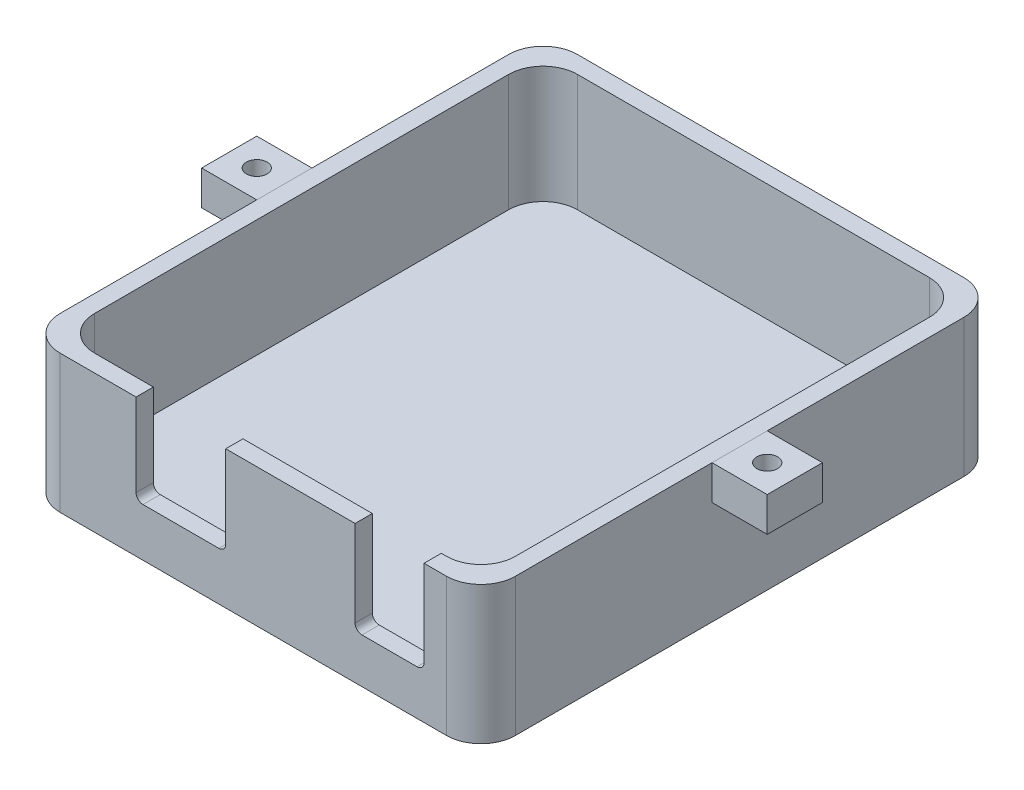
SolidWorks part; units mm, degrees
ref_plane "Ebene vorne" through (0, 0, 0) normal (0, 0, 1) x (1, 0, 0)
ref_plane "Ebene oben" through (0, 0, 0) normal (0, 1, 0) x (1, 0, 0)
ref_plane "Ebene rechts" through (0, 0, 0) normal (1, 0, 0) x (0, 0, -1)
sketch "Skizze1" plane through (0, 0, 0) normal (0, 1, 0) x (1, 0, 0)
  line L1 (28, -37.5) -> (-28, -37.5)
  line L2 (33, -32.5) -> (33, 32.5)
  line L3 (28, 37.5) -> (-28, 37.5)
  line L4 (-33, -32.5) -> (-33, 32.5)
  line L5 (33, -37.5) -> (-33, 37.5) construction
  line L6 (33, 37.5) -> (-33, -37.5) construction
  arc A0 (33, 32.5) -> (28, 37.5) centre (28, 32.5) ccw
  arc A1 (28, -37.5) -> (33, -32.5) centre (28, -32.5) ccw
  arc A2 (-28, -37.5) -> (-33, -32.5) centre (-28, -32.5) cw
  arc A3 (-28, 37.5) -> (-33, 32.5) centre (-28, 32.5) ccw
  point P0 (0, 0)
  dimension "D3" = 5
  dimension "D1" = 75
  dimension "D2" = 66
extrude "Aufsatz-Linear austragen1" add sketch "Skizze1" along normal blind 20
sketch "Skizze2" plane through (0, 20, 0) normal (0, 1, 0) x (1, 0, 0)
  line L0 (28, 37.5) -> (-28, 37.5) construction
  line L1 (-25.5, 35) -> (25.5, 35)
  line L2 (-30.5, 30) -> (-30.5, -30)
  line L3 (-25.5, -35) -> (25.5, -35)
  line L4 (30.5, 30) -> (30.5, -30)
  line L5 (-30.5, 35) -> (30.5, -35) construction
  line L6 (-30.5, -35) -> (30.5, 35) construction
  line L7 (33, -32.5) -> (33, 32.5) construction
  arc A0 (-30.5, -30) -> (-25.5, -35) centre (-25.5, -30) ccw
  arc A1 (25.5, -35) -> (30.5, -30) centre (25.5, -30) ccw
  arc A2 (25.5, 35) -> (30.5, 30) centre (25.5, 30) cw
  arc A3 (-25.5, 35) -> (-30.5, 30) centre (-25.5, 30) ccw
  point P0 (0, 0)
  dimension "D3" = 5
  dimension "D1" = 2.5
  dimension "D2" = 2.5
extrude "Schnitt-Linear austragen1" cut sketch "Skizze2" against normal blind 17
sketch "Skizze4" plane through (0, 0, 37.5) normal (0, 0, 1) x (1, 0, 0)
  line L0 (-28, 0) -> (28, 0) construction
  line L1 (-16, 22) -> (-5, 22)
  line L2 (-17, 21) -> (-17, 8)
  line L3 (-16, 7) -> (-5, 7)
  line L4 (-4, 21) -> (-4, 8)
  line L5 (-17, 22) -> (-4, 7) construction
  line L6 (-17, 7) -> (-4, 22) construction
  line L7 (-33, 20) -> (-33, 0) construction
  line L8 (33, 20) -> (33, 0) construction
  line L9 (15.75, 21.5) -> (23.75, 21.5)
  line L10 (14.75, 20.5) -> (14.75, 7.5)
  line L11 (15.75, 6.5) -> (23.75, 6.5)
  line L12 (24.75, 20.5) -> (24.75, 7.5)
  line L13 (14.75, 21.5) -> (24.75, 6.5) construction
  line L14 (14.75, 6.5) -> (24.75, 21.5) construction
  arc A0 (15.75, 21.5) -> (14.75, 20.5) centre (15.75, 20.5) ccw
  arc A1 (23.75, 21.5) -> (24.75, 20.5) centre (23.75, 20.5) cw
  arc A2 (23.75, 6.5) -> (24.75, 7.5) centre (23.75, 7.5) ccw
  arc A3 (14.75, 7.5) -> (15.75, 6.5) centre (15.75, 7.5) ccw
  arc A4 (-17, 8) -> (-16, 7) centre (-16, 8) ccw
  arc A5 (-5, 7) -> (-4, 8) centre (-5, 8) ccw
  arc A6 (-5, 22) -> (-4, 21) centre (-5, 21) cw
  arc A7 (-16, 22) -> (-17, 21) centre (-16, 21) ccw
  point P0 (-10.5, 14.5)
  point P9 (19.75, 14)
  dimension "D9" = 1
  dimension "D10" = 1
  dimension "D1" = 7
  dimension "D2" = 16
  dimension "D3" = 15
  dimension "D4" = 13
  dimension "D5" = 6.5
  dimension "D6" = 8.25
  dimension "D7" = 15
  dimension "D8" = 10
extrude "Schnitt-Linear austragen2" cut sketch "Skizze4" against normal blind 17
sketch "Skizze5" plane through (0, 20, 0) normal (0, 1, 0) x (1, 0, 0)
  line L3 (33, -32.5) -> (33, 32.5) construction
  line L4 (33, -4) -> (41, -4)
  line L5 (33, -4) -> (33, 4)
  line L6 (33, 4) -> (41, 4)
  line L7 (41, -4) -> (41, 4)
  line L8 (24.75, -37.5) -> (28, -37.5) construction
  line L9 (-33, 32.5) -> (-33, -32.5) construction
  line L10 (-33, 4) -> (-41, 4)
  line L11 (-33, 4) -> (-33, -4)
  line L12 (-33, -4) -> (-41, -4)
  line L13 (-41, 4) -> (-41, -4)
  line L14 (-28, -37.5) -> (-17, -37.5) construction
  dimension "D1" = 8
  dimension "D2" = 8
  dimension "D3" = 33.5
  dimension "D4" = 8
  dimension "D5" = 8
  dimension "D6" = 33.5
extrude "Aufsatz-Linear austragen2" add sketch "Skizze5" against normal blind 5 separate body
sketch "Skizze6" plane through (0, 20, 0) normal (0, 1, 0) x (1, 0, 0)
  line L0 (-33, 4) -> (-41, 4) construction
  line L1 (-41, 4) -> (-41, -4) construction
  line L2 (41, -4) -> (41, 4) construction
  line L3 (41, 4) -> (33, 4) construction
  circle A0 centre (-37, 0) radius 1.5
  circle A1 centre (37, 0) radius 1.5
  dimension "D1" = 3
  dimension "D2" = 3
  dimension "D3" = 4
  dimension "D4" = 4
  dimension "D5" = 4
  dimension "D6" = 4
extrude "Schnitt-Linear austragen3" cut sketch "Skizze6" against normal blind 10
